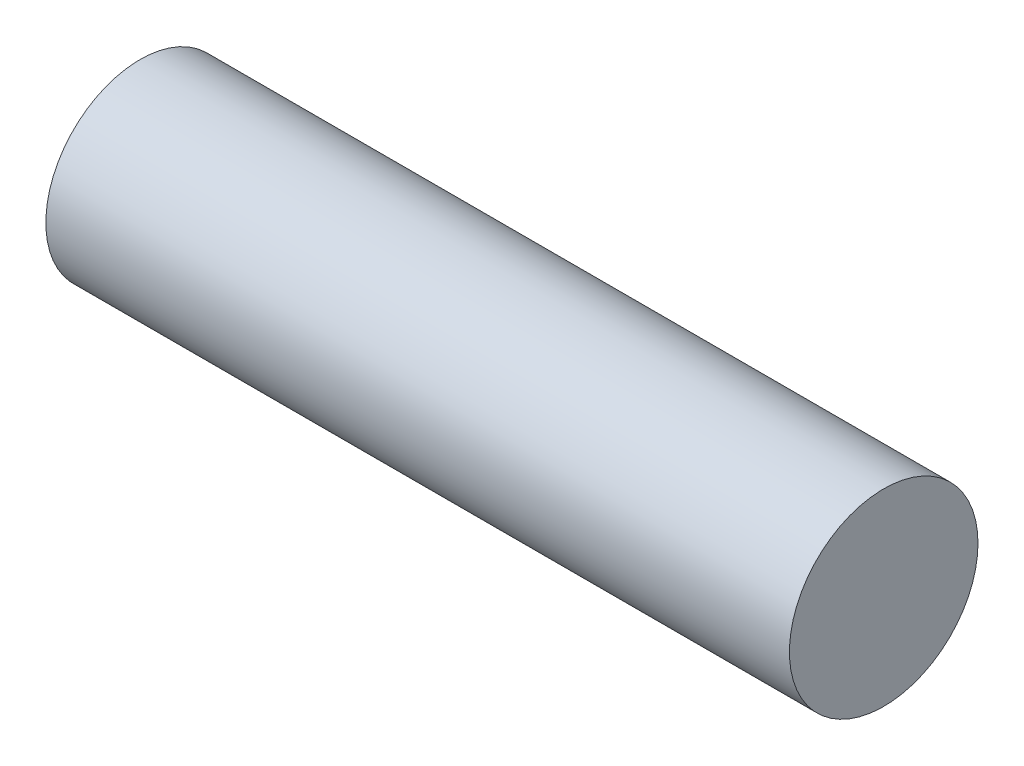
SolidWorks part; units mm, degrees
material "Fibra de Vidro A"
ref_plane "Front" through (0, 0, 0) normal (0, 0, 1) x (1, 0, 0)
ref_plane "Top" through (0, 0, 0) normal (0, 1, 0) x (1, 0, 0)
ref_plane "Right" through (0, 0, 0) normal (1, 0, 0) x (0, 0, -1)
sketch "Esboço1" plane through (0, 0, 0) normal (1, 0, 0) x (0, 0, -1)
  circle A0 centre (-166.5038, 127.9393) radius 31.6994
  point P37 (106.7903, 159.9917)
  point P38 (-101.6768, 159.9917)
extrude "Ressalto-extrusão1" add sketch "Esboço1" along normal mid plane 250
